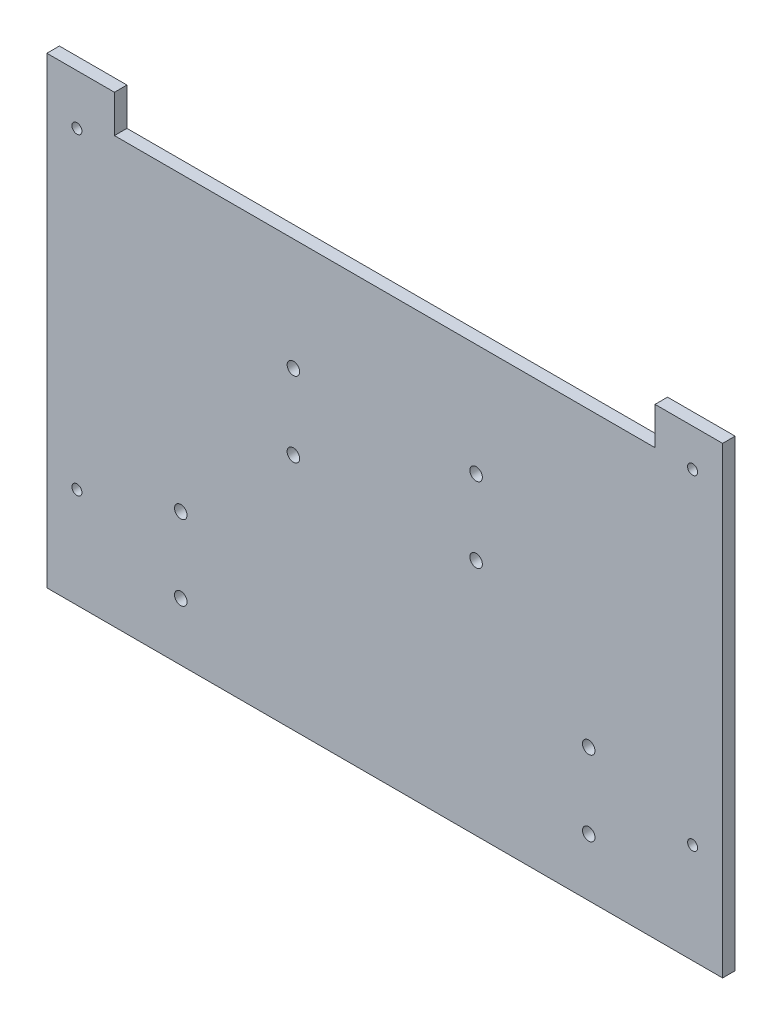
SolidWorks part; units mm, degrees
ref_plane "Plan de face" through (0, 0, 0) normal (0, 0, 1) x (1, 0, 0)
ref_plane "Plan de dessus" through (0, 0, 0) normal (0, 1, 0) x (1, 0, 0)
ref_plane "Plan de droite" through (0, 0, 0) normal (1, 0, 0) x (0, 0, -1)
sketch "Esquisse1" plane through (0, 0, 0) normal (0, 0, 1) x (1, 0, 0)
  line L0 (-135, 85) -> (-135, 100)
  line L2 (-135, 85) -> (-135, -85)
  line L3 (-135, -85) -> (135, -85)
  line L4 (135, 85) -> (135, -85)
  line L5 (-135, 85) -> (135, -85) construction
  line L6 (-135, -85) -> (135, 85) construction
  line L7 (-135, 100) -> (-108, 100)
  line L8 (-108, 100) -> (-108, 85)
  line L9 (-108, 85) -> (108, 85)
  line L10 (108, 85) -> (108, 100)
  line L11 (108, 100) -> (135, 100)
  line L12 (135, 100) -> (135, 85)
  point P0 (0, 0)
  dimension "D1" = 270
  dimension "D2" = 170
  dimension "D3" = 27
  dimension "D4" = 27
  dimension "D5" = 15
  dimension "D6" = 15
  dimension "D7" = 170
  dimension "D8" = 135
extrude "Boss.-Extru.1" add sketch "Esquisse1" along normal blind 5
sketch "Esquisse2" plane through (0, 0, 5) normal (0, 0, 1) x (1, 0, 0)
  line L0 (-135, -85) -> (135, -85) construction
  line L1 (-135, 100) -> (-135, -85) construction
  line L3 (-135, -85) -> (135, -85) construction
  line L4 (135, -85) -> (135, 100) construction
  circle A0 centre (-123, -45) radius 2
  circle A1 centre (-123, 80) radius 2
  circle A2 centre (123, -45) radius 2
  circle A3 centre (123, 85) radius 2
  dimension "D3" = 4
  dimension "D4" = 4
  dimension "D7" = 4
  dimension "D8" = 4
  dimension "D1" = 40
  dimension "D2" = 12
  dimension "D5" = 125
  dimension "D6" = 12
  dimension "D9" = 40
  dimension "D10" = 130
  dimension "D11" = 12
  dimension "D12" = 12
extrude "Enlèv. mat.-Extru.1" cut sketch "Esquisse2" against normal through all
sketch "Sketch1" plane through (0, 0, 5) normal (0, 0, 1) x (1, 0, 0)
  circle A0 centre (81.5, -31.8856) radius 2.5 construction
  circle A1 centre (81.5, -61.8856) radius 2.5 construction
  circle A2 centre (-81.5, -61.8856) radius 2.5 construction
  circle A3 centre (-81.5, -31.8856) radius 2.5 construction
  circle A4 centre (81.5, -31.8856) radius 2.5
  circle A5 centre (81.5, -61.8856) radius 2.5
  circle A6 centre (-81.5, -61.8856) radius 2.5
  circle A7 centre (-81.5, -31.8856) radius 2.5
extrude "Cut-Extrude1" cut sketch "Sketch1" against normal through all
sketch "Sketch2" plane through (0, 0, 5) normal (0, 0, 1) x (1, 0, 0)
  circle A0 centre (36.5, 40.2132) radius 2.5 construction
  circle A1 centre (36.5, 10.2132) radius 2.5 construction
  circle A2 centre (-36.5, 10.2132) radius 2.5 construction
  circle A3 centre (-36.5, 40.2132) radius 2.5 construction
  circle A4 centre (36.5, 40.2132) radius 2.5
  circle A5 centre (36.5, 10.2132) radius 2.5
  circle A6 centre (-36.5, 10.2132) radius 2.5
  circle A7 centre (-36.5, 40.2132) radius 2.5
extrude "Cut-Extrude2" cut sketch "Sketch2" against normal blind 24
